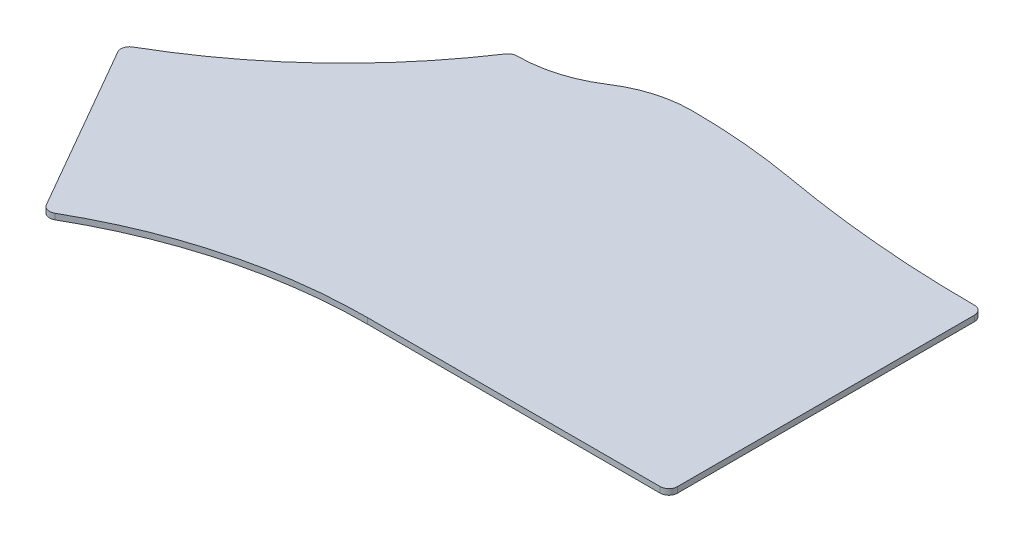
SolidWorks part; units mm, degrees
ref_plane "Front Plane" through (0, 0, 0) normal (0, 0, 1) x (1, 0, 0)
ref_plane "Top Plane" through (0, 0, 0) normal (0, 1, 0) x (1, 0, 0)
ref_plane "Right Plane" through (0, 0, 0) normal (1, 0, 0) x (0, 0, -1)
sketch "Main" plane through (0, 0, 0) normal (0, 1, 0) x (1, 0, 0)
  line L0 (6.4754, 3.5) -> (12.8, 6.5) construction
  line L1 (0, 0) -> (18, 0) construction
  line L2 (0, 0) -> (0, 18) construction
  line L3 (0, 18) -> (18, 18) construction
  line L4 (18, 0) -> (18, 18) construction
  line L5 (2, 16) -> (16, 16)
  line L6 (2, 16) -> (2, 2)
  line L7 (2, 2) -> (16, 2)
  line L8 (16, 16) -> (16, 2)
  line L18 (9, 9) -> (6.4754, 3.5) construction
  line L20 (9, 9) -> (12.8, 6.5) construction
  line L22 (25.4754, 5.5) -> (31.8, 8.5) construction
  line L23 (19, 2) -> (37, 2) construction
  line L24 (19, 2) -> (19, 20) construction
  line L25 (19, 20) -> (37, 20) construction
  line L26 (37, 2) -> (37, 20) construction
  line L27 (21, 18) -> (35, 18)
  line L28 (21, 18) -> (21, 4)
  line L29 (21, 4) -> (35, 4)
  line L30 (35, 18) -> (35, 4)
  line L31 (28, 11) -> (25.4754, 5.5) construction
  line L32 (28, 11) -> (31.8, 8.5) construction
  line L33 (44.4754, 17.5) -> (50.8, 20.5) construction
  line L34 (38, 14) -> (56, 14) construction
  line L35 (38, 14) -> (38, 32) construction
  line L36 (38, 32) -> (56, 32) construction
  line L37 (56, 14) -> (56, 32) construction
  line L38 (40, 30) -> (54, 30)
  line L39 (40, 30) -> (40, 16)
  line L40 (40, 16) -> (54, 16)
  line L41 (54, 30) -> (54, 16)
  line L42 (47, 23) -> (44.4754, 17.5) construction
  line L43 (47, 23) -> (50.8, 20.5) construction
  line L44 (63.4754, 12.5) -> (69.8, 15.5) construction
  line L45 (57, 9) -> (75, 9) construction
  line L46 (57, 9) -> (57, 27) construction
  line L47 (57, 27) -> (75, 27) construction
  line L48 (75, 9) -> (75, 27) construction
  line L49 (59, 25) -> (73, 25)
  line L50 (59, 25) -> (59, 11)
  line L51 (59, 11) -> (73, 11)
  line L52 (73, 25) -> (73, 11)
  line L53 (66, 18) -> (63.4754, 12.5) construction
  line L54 (66, 18) -> (69.8, 15.5) construction
  line L55 (82.4754, 3.5) -> (88.8, 6.5) construction
  line L56 (76, 0) -> (94, 0) construction
  line L57 (76, 0) -> (76, 18) construction
  line L58 (76, 18) -> (94, 18) construction
  line L59 (94, 0) -> (94, 18) construction
  line L60 (78, 16) -> (92, 16)
  line L61 (78, 16) -> (78, 2)
  line L62 (78, 2) -> (92, 2)
  line L63 (92, 16) -> (92, 2)
  line L64 (85, 9) -> (82.4754, 3.5) construction
  line L65 (85, 9) -> (88.8, 6.5) construction
  line L66 (101.4754, -18.5) -> (107.8, -15.5) construction
  line L67 (95, -22) -> (113, -22) construction
  line L68 (95, -22) -> (95, -4) construction
  line L69 (95, -4) -> (113, -4) construction
  line L70 (113, -22) -> (113, -4) construction
  line L71 (97, -6) -> (111, -6)
  line L72 (97, -6) -> (97, -20)
  line L73 (97, -20) -> (111, -20)
  line L74 (111, -6) -> (111, -20)
  line L75 (104, -13) -> (101.4754, -18.5) construction
  line L76 (104, -13) -> (107.8, -15.5) construction
  line L77 (120.4754, -18.5) -> (126.8, -15.5) construction
  line L78 (114, -22) -> (132, -22) construction
  line L79 (114, -22) -> (114, -4) construction
  line L80 (114, -4) -> (132, -4) construction
  line L81 (132, -22) -> (132, -4) construction
  line L82 (116, -6) -> (130, -6)
  line L83 (116, -6) -> (116, -20)
  line L84 (116, -20) -> (130, -20)
  line L85 (130, -6) -> (130, -20)
  line L86 (123, -13) -> (120.4754, -18.5) construction
  line L87 (123, -13) -> (126.8, -15.5) construction
  line L88 (2, -3) -> (16, -3)
  line L89 (2, -3) -> (2, -17)
  line L90 (2, -17) -> (16, -17)
  line L91 (16, -3) -> (16, -17)
  line L92 (21, -1) -> (35, -1)
  line L93 (21, -1) -> (21, -15)
  line L94 (21, -15) -> (35, -15)
  line L95 (35, -1) -> (35, -15)
  line L96 (40, 11) -> (54, 11)
  line L97 (40, 11) -> (40, -3)
  line L98 (40, -3) -> (54, -3)
  line L99 (54, 11) -> (54, -3)
  line L100 (59, 6) -> (73, 6)
  line L101 (59, 6) -> (59, -8)
  line L102 (59, -8) -> (73, -8)
  line L103 (73, 6) -> (73, -8)
  line L104 (78, -3) -> (92, -3)
  line L105 (78, -3) -> (78, -17)
  line L106 (78, -17) -> (92, -17)
  line L107 (92, -3) -> (92, -17)
  line L108 (97, -25) -> (111, -25)
  line L109 (97, -25) -> (97, -39)
  line L110 (97, -39) -> (111, -39)
  line L111 (111, -25) -> (111, -39)
  line L112 (116, -25) -> (130, -25)
  line L113 (116, -25) -> (116, -39)
  line L114 (116, -39) -> (130, -39)
  line L115 (130, -25) -> (130, -39)
  line L116 (6.4754, -15.5) -> (12.8, -12.5) construction
  line L117 (0, -19) -> (18, -19) construction
  line L118 (0, -19) -> (0, -1) construction
  line L119 (0, -1) -> (18, -1) construction
  line L120 (18, -19) -> (18, -1) construction
  line L121 (9, -10) -> (6.4754, -15.5) construction
  line L122 (9, -10) -> (12.8, -12.5) construction
  line L123 (25.4754, -13.5) -> (31.8, -10.5) construction
  line L124 (19, -17) -> (37, -17) construction
  line L125 (19, -17) -> (19, 1) construction
  line L126 (19, 1) -> (37, 1) construction
  line L127 (37, -17) -> (37, 1) construction
  line L128 (28, -8) -> (25.4754, -13.5) construction
  line L129 (28, -8) -> (31.8, -10.5) construction
  line L130 (44.4754, -1.5) -> (50.8, 1.5) construction
  line L131 (38, -5) -> (56, -5) construction
  line L132 (38, -5) -> (38, 13) construction
  line L133 (38, 13) -> (56, 13) construction
  line L134 (56, -5) -> (56, 13) construction
  line L135 (47, 4) -> (44.4754, -1.5) construction
  line L136 (47, 4) -> (50.8, 1.5) construction
  line L137 (63.4754, -6.5) -> (69.8, -3.5) construction
  line L138 (57, -10) -> (75, -10) construction
  line L139 (57, -10) -> (57, 8) construction
  line L140 (57, 8) -> (75, 8) construction
  line L141 (75, -10) -> (75, 8) construction
  line L142 (66, -1) -> (63.4754, -6.5) construction
  line L143 (66, -1) -> (69.8, -3.5) construction
  line L144 (82.4754, -15.5) -> (88.8, -12.5) construction
  line L145 (76, -19) -> (94, -19) construction
  line L146 (76, -19) -> (76, -1) construction
  line L147 (76, -1) -> (94, -1) construction
  line L148 (94, -19) -> (94, -1) construction
  line L149 (85, -10) -> (82.4754, -15.5) construction
  line L150 (85, -10) -> (88.8, -12.5) construction
  line L151 (101.4754, -37.5) -> (107.8, -34.5) construction
  line L152 (95, -41) -> (113, -41) construction
  line L153 (95, -41) -> (95, -23) construction
  line L154 (95, -23) -> (113, -23) construction
  line L155 (113, -41) -> (113, -23) construction
  line L156 (104, -32) -> (101.4754, -37.5) construction
  line L157 (104, -32) -> (107.8, -34.5) construction
  line L158 (120.4754, -37.5) -> (126.8, -34.5) construction
  line L159 (114, -41) -> (132, -41) construction
  line L160 (114, -41) -> (114, -23) construction
  line L161 (114, -23) -> (132, -23) construction
  line L162 (132, -41) -> (132, -23) construction
  line L163 (123, -32) -> (120.4754, -37.5) construction
  line L164 (123, -32) -> (126.8, -34.5) construction
  line L165 (2, -22) -> (16, -22)
  line L166 (2, -22) -> (2, -36)
  line L167 (2, -36) -> (16, -36)
  line L168 (16, -22) -> (16, -36)
  line L169 (21, -20) -> (35, -20)
  line L170 (21, -20) -> (21, -34)
  line L171 (21, -34) -> (35, -34)
  line L172 (35, -20) -> (35, -34)
  line L173 (40, -8) -> (54, -8)
  line L174 (40, -8) -> (40, -22)
  line L175 (40, -22) -> (54, -22)
  line L176 (54, -8) -> (54, -22)
  line L177 (59, -13) -> (73, -13)
  line L178 (59, -13) -> (59, -27)
  line L179 (59, -27) -> (73, -27)
  line L180 (73, -13) -> (73, -27)
  line L181 (78, -22) -> (92, -22)
  line L182 (78, -22) -> (78, -36)
  line L183 (78, -36) -> (92, -36)
  line L184 (92, -22) -> (92, -36)
  line L193 (6.4754, -34.5) -> (12.8, -31.5) construction
  line L194 (0, -38) -> (18, -38) construction
  line L195 (0, -38) -> (0, -20) construction
  line L196 (0, -20) -> (18, -20) construction
  line L197 (18, -38) -> (18, -20) construction
  line L198 (9, -29) -> (6.4754, -34.5) construction
  line L199 (9, -29) -> (12.8, -31.5) construction
  line L200 (25.4754, -32.5) -> (31.8, -29.5) construction
  line L201 (19, -36) -> (37, -36) construction
  line L202 (19, -36) -> (19, -18) construction
  line L203 (19, -18) -> (37, -18) construction
  line L204 (37, -36) -> (37, -18) construction
  line L205 (28, -27) -> (25.4754, -32.5) construction
  line L206 (28, -27) -> (31.8, -29.5) construction
  line L207 (44.4754, -20.5) -> (50.8, -17.5) construction
  line L208 (38, -24) -> (56, -24) construction
  line L209 (38, -24) -> (38, -6) construction
  line L210 (38, -6) -> (56, -6) construction
  line L211 (56, -24) -> (56, -6) construction
  line L212 (47, -15) -> (44.4754, -20.5) construction
  line L213 (47, -15) -> (50.8, -17.5) construction
  line L214 (63.4754, -25.5) -> (69.8, -22.5) construction
  line L215 (57, -29) -> (75, -29) construction
  line L216 (57, -29) -> (57, -11) construction
  line L217 (57, -11) -> (75, -11) construction
  line L218 (75, -29) -> (75, -11) construction
  line L219 (66, -20) -> (63.4754, -25.5) construction
  line L220 (66, -20) -> (69.8, -22.5) construction
  line L221 (82.4754, -34.5) -> (88.8, -31.5) construction
  line L222 (76, -38) -> (94, -38) construction
  line L223 (76, -38) -> (76, -20) construction
  line L224 (76, -20) -> (94, -20) construction
  line L225 (94, -38) -> (94, -20) construction
  line L226 (85, -29) -> (82.4754, -34.5) construction
  line L227 (85, -29) -> (88.8, -31.5) construction
  line L228 (97, 20.5) -> (111, 20.5)
  line L231 (97, 20.5) -> (97, 6.5)
  line L232 (97, 6.5) -> (111, 6.5)
  line L233 (111, 20.5) -> (111, 6.5)
  line L234 (116, 20.5) -> (130, 20.5)
  line L235 (116, 20.5) -> (116, 6.5)
  line L236 (116, 6.5) -> (130, 6.5)
  line L237 (130, 20.5) -> (130, 6.5)
  line L238 (101.4754, 8) -> (107.8, 11) construction
  line L239 (95, 4.5) -> (113, 4.5) construction
  line L240 (95, 4.5) -> (95, 22.5) construction
  line L241 (95, 22.5) -> (113, 22.5) construction
  line L242 (2, -41) -> (16, -41)
  line L243 (2, -41) -> (2, -55)
  line L244 (2, -55) -> (16, -55)
  line L245 (16, -41) -> (16, -55)
  line L246 (21, -39) -> (35, -39)
  line L247 (21, -39) -> (21, -53)
  line L248 (21, -53) -> (35, -53)
  line L249 (35, -39) -> (35, -53)
  line L250 (40, -27) -> (54, -27)
  line L251 (40, -27) -> (40, -41)
  line L252 (40, -41) -> (54, -41)
  line L253 (54, -27) -> (54, -41)
  line L254 (59, -32) -> (73, -32)
  line L255 (59, -32) -> (59, -46)
  line L256 (59, -46) -> (73, -46)
  line L257 (73, -32) -> (73, -46)
  line L258 (78, -41) -> (92, -41)
  line L259 (78, -41) -> (78, -55)
  line L260 (78, -55) -> (92, -55)
  line L261 (92, -41) -> (92, -55)
  line L270 (6.4754, -53.5) -> (12.8, -50.5) construction
  line L271 (0, -57) -> (18, -57) construction
  line L272 (0, -57) -> (0, -39) construction
  line L273 (0, -39) -> (18, -39) construction
  line L274 (18, -57) -> (18, -39) construction
  line L275 (9, -48) -> (6.4754, -53.5) construction
  line L276 (9, -48) -> (12.8, -50.5) construction
  line L277 (25.4754, -51.5) -> (31.8, -48.5) construction
  line L278 (19, -55) -> (37, -55) construction
  line L279 (19, -55) -> (19, -37) construction
  line L280 (19, -37) -> (37, -37) construction
  line L281 (37, -55) -> (37, -37) construction
  line L282 (28, -46) -> (25.4754, -51.5) construction
  line L283 (28, -46) -> (31.8, -48.5) construction
  line L284 (44.4754, -39.5) -> (50.8, -36.5) construction
  line L285 (38, -43) -> (56, -43) construction
  line L286 (38, -43) -> (38, -25) construction
  line L287 (38, -25) -> (56, -25) construction
  line L288 (56, -43) -> (56, -25) construction
  line L289 (47, -34) -> (44.4754, -39.5) construction
  line L290 (47, -34) -> (50.8, -36.5) construction
  line L291 (63.4754, -44.5) -> (69.8, -41.5) construction
  line L292 (57, -48) -> (75, -48) construction
  line L293 (57, -48) -> (57, -30) construction
  line L294 (57, -30) -> (75, -30) construction
  line L295 (75, -48) -> (75, -30) construction
  line L296 (66, -39) -> (63.4754, -44.5) construction
  line L297 (66, -39) -> (69.8, -41.5) construction
  line L298 (82.4754, -53.5) -> (88.8, -50.5) construction
  line L299 (76, -57) -> (94, -57) construction
  line L300 (76, -57) -> (76, -39) construction
  line L301 (76, -39) -> (94, -39) construction
  line L302 (94, -57) -> (94, -39) construction
  line L303 (85, -48) -> (82.4754, -53.5) construction
  line L304 (85, -48) -> (88.8, -50.5) construction
  line L305 (113, 4.5) -> (113, 22.5) construction
  line L306 (104, 13.5) -> (101.4754, 8) construction
  line L307 (104, 13.5) -> (107.8, 11) construction
  line L308 (120.4754, 8) -> (126.8, 11) construction
  line L309 (114, 4.5) -> (132, 4.5) construction
  line L310 (114, 4.5) -> (114, 22.5) construction
  line L311 (114, 22.5) -> (132, 22.5) construction
  line L312 (132, 4.5) -> (132, 22.5) construction
  line L313 (123, 13.5) -> (120.4754, 8) construction
  line L314 (123, 13.5) -> (126.8, 11) construction
  line L319 (97, -63) -> (111, -63)
  line L320 (97, -63) -> (97, -77)
  line L321 (97, -77) -> (111, -77)
  line L322 (111, -63) -> (111, -77)
  line L323 (116, -63) -> (130, -63)
  line L324 (116, -63) -> (116, -77)
  line L325 (116, -77) -> (130, -77)
  line L326 (130, -63) -> (130, -77)
  line L327 (101.4754, -75.5) -> (107.8, -72.5) construction
  line L328 (95, -79) -> (113, -79) construction
  line L329 (95, -79) -> (95, -61) construction
  line L330 (95, -61) -> (113, -61) construction
  line L331 (113, -79) -> (113, -61) construction
  line L332 (104, -70) -> (101.4754, -75.5) construction
  line L333 (104, -70) -> (107.8, -72.5) construction
  line L334 (120.4754, -75.5) -> (126.8, -72.5) construction
  line L335 (114, -79) -> (132, -79) construction
  line L336 (114, -79) -> (114, -61) construction
  line L337 (114, -61) -> (132, -61) construction
  line L338 (132, -79) -> (132, -61) construction
  line L339 (123, -70) -> (120.4754, -75.5) construction
  line L340 (123, -70) -> (126.8, -72.5) construction
  line L341 (97, -44) -> (111, -44)
  line L342 (97, -44) -> (97, -58)
  line L343 (97, -58) -> (111, -58)
  line L344 (111, -44) -> (111, -58)
  line L345 (116, -44) -> (130, -44)
  line L346 (116, -44) -> (116, -58)
  line L347 (116, -58) -> (130, -58)
  line L348 (130, -44) -> (130, -58)
  line L349 (101.4754, -56.5) -> (107.8, -53.5) construction
  line L350 (95, -42) -> (113, -42) construction
  line L351 (113, -60) -> (113, -42) construction
  line L352 (104, -51) -> (101.4754, -56.5) construction
  line L353 (104, -51) -> (107.8, -53.5) construction
  line L354 (120.4754, -56.5) -> (126.8, -53.5) construction
  line L355 (114, -60) -> (132, -60) construction
  line L356 (114, -60) -> (114, -42) construction
  line L357 (114, -42) -> (132, -42) construction
  line L358 (132, -60) -> (132, -42) construction
  line L359 (123, -51) -> (120.4754, -56.5) construction
  line L360 (123, -51) -> (126.8, -53.5) construction
  line L361 (95, -60) -> (113, -60) construction
  line L362 (95, -60) -> (95, -42) construction
  circle A0 centre (9, 9) radius 2 construction
  circle A1 centre (6.4754, 3.5) radius 1.5 construction
  circle A2 centre (12.8, 6.5) radius 1.5 construction
  circle A6 centre (28, 11) radius 2 construction
  circle A7 centre (25.4754, 5.5) radius 1.5 construction
  circle A8 centre (31.8, 8.5) radius 1.5 construction
  circle A9 centre (47, 23) radius 2 construction
  circle A10 centre (44.4754, 17.5) radius 1.5 construction
  circle A11 centre (50.8, 20.5) radius 1.5 construction
  circle A12 centre (66, 18) radius 2 construction
  circle A13 centre (63.4754, 12.5) radius 1.5 construction
  circle A14 centre (69.8, 15.5) radius 1.5 construction
  circle A15 centre (85, 9) radius 2 construction
  circle A16 centre (82.4754, 3.5) radius 1.5 construction
  circle A17 centre (88.8, 6.5) radius 1.5 construction
  circle A18 centre (104, -13) radius 2 construction
  circle A19 centre (101.4754, -18.5) radius 1.5 construction
  circle A20 centre (107.8, -15.5) radius 1.5 construction
  circle A21 centre (123, -13) radius 2 construction
  circle A22 centre (120.4754, -18.5) radius 1.5 construction
  circle A23 centre (126.8, -15.5) radius 1.5 construction
  circle A24 centre (9, -10) radius 2 construction
  circle A25 centre (6.4754, -15.5) radius 1.5 construction
  circle A26 centre (12.8, -12.5) radius 1.5 construction
  circle A27 centre (28, -8) radius 2 construction
  circle A28 centre (25.4754, -13.5) radius 1.5 construction
  circle A29 centre (31.8, -10.5) radius 1.5 construction
  circle A30 centre (47, 4) radius 2 construction
  circle A31 centre (44.4754, -1.5) radius 1.5 construction
  circle A32 centre (50.8, 1.5) radius 1.5 construction
  circle A33 centre (66, -1) radius 2 construction
  circle A34 centre (63.4754, -6.5) radius 1.5 construction
  circle A35 centre (69.8, -3.5) radius 1.5 construction
  circle A36 centre (85, -10) radius 2 construction
  circle A37 centre (82.4754, -15.5) radius 1.5 construction
  circle A38 centre (88.8, -12.5) radius 1.5 construction
  circle A39 centre (104, -32) radius 2 construction
  circle A40 centre (101.4754, -37.5) radius 1.5 construction
  circle A41 centre (107.8, -34.5) radius 1.5 construction
  circle A42 centre (123, -32) radius 2 construction
  circle A43 centre (120.4754, -37.5) radius 1.5 construction
  circle A44 centre (126.8, -34.5) radius 1.5 construction
  circle A45 centre (9, -29) radius 2 construction
  circle A46 centre (6.4754, -34.5) radius 1.5 construction
  circle A47 centre (12.8, -31.5) radius 1.5 construction
  circle A48 centre (28, -27) radius 2 construction
  circle A49 centre (25.4754, -32.5) radius 1.5 construction
  circle A50 centre (31.8, -29.5) radius 1.5 construction
  circle A51 centre (47, -15) radius 2 construction
  circle A52 centre (44.4754, -20.5) radius 1.5 construction
  circle A53 centre (50.8, -17.5) radius 1.5 construction
  circle A54 centre (66, -20) radius 2 construction
  circle A55 centre (63.4754, -25.5) radius 1.5 construction
  circle A56 centre (69.8, -22.5) radius 1.5 construction
  circle A57 centre (85, -29) radius 2 construction
  circle A58 centre (82.4754, -34.5) radius 1.5 construction
  circle A59 centre (88.8, -31.5) radius 1.5 construction
  circle A60 centre (104, 13.5) radius 2 construction
  circle A61 centre (101.4754, 8) radius 1.5 construction
  circle A62 centre (107.8, 11) radius 1.5 construction
  circle A63 centre (123, 13.5) radius 2 construction
  circle A64 centre (120.4754, 8) radius 1.5 construction
  circle A65 centre (126.8, 11) radius 1.5 construction
  circle A66 centre (9, -48) radius 2 construction
  circle A67 centre (6.4754, -53.5) radius 1.5 construction
  circle A68 centre (12.8, -50.5) radius 1.5 construction
  circle A69 centre (28, -46) radius 2 construction
  circle A70 centre (25.4754, -51.5) radius 1.5 construction
  circle A71 centre (31.8, -48.5) radius 1.5 construction
  circle A72 centre (47, -34) radius 2 construction
  circle A73 centre (44.4754, -39.5) radius 1.5 construction
  circle A74 centre (50.8, -36.5) radius 1.5 construction
  circle A75 centre (66, -39) radius 2 construction
  circle A76 centre (63.4754, -44.5) radius 1.5 construction
  circle A77 centre (69.8, -41.5) radius 1.5 construction
  circle A78 centre (85, -48) radius 2 construction
  circle A79 centre (82.4754, -53.5) radius 1.5 construction
  circle A80 centre (88.8, -50.5) radius 1.5 construction
  circle A87 centre (104, -70) radius 2 construction
  circle A88 centre (101.4754, -75.5) radius 1.5 construction
  circle A89 centre (107.8, -72.5) radius 1.5 construction
  circle A90 centre (123, -70) radius 2 construction
  circle A91 centre (120.4754, -75.5) radius 1.5 construction
  circle A92 centre (126.8, -72.5) radius 1.5 construction
  circle A93 centre (104, -51) radius 2 construction
  circle A94 centre (101.4754, -56.5) radius 1.5 construction
  circle A95 centre (107.8, -53.5) radius 1.5 construction
  circle A96 centre (123, -51) radius 2 construction
  circle A97 centre (120.4754, -56.5) radius 1.5 construction
  circle A98 centre (126.8, -53.5) radius 1.5 construction
  point P9 (9, 16)
  point P10 (9, 18)
  point P11 (2, 9)
  point P12 (0, 9)
  point P30 (28, 18)
  point P31 (28, 20)
  point P32 (21, 11)
  point P33 (19, 11)
  point P46 (47, 30)
  point P47 (47, 32)
  point P48 (40, 23)
  point P49 (38, 23)
  point P64 (66, 25)
  point P65 (66, 27)
  point P66 (59, 18)
  point P67 (57, 18)
  point P82 (85, 16)
  point P83 (85, 18)
  point P84 (78, 9)
  point P85 (76, 9)
  point P100 (104, -6)
  point P101 (104, -4)
  point P102 (97, -13)
  point P103 (95, -13)
  point P118 (123, -6)
  point P119 (123, -4)
  point P120 (116, -13)
  point P121 (114, -13)
  dimension "D6" = 4
  dimension "D7" = 3
  dimension "D10" = 1
  dimension "D11" = 5
  dimension "D1" = 18
  dimension "D2" = 14
  dimension "D3" = 3.2
  dimension "D4" = 4.5
  dimension "D5" = 7
  dimension "D8" = 1
  dimension "D9" = 12
  dimension "D12" = 1
  dimension "D13" = 2
  dimension "D14" = 1
  dimension "D15" = 9
  dimension "D16" = 1
  dimension "D17" = 3
  dimension "D18" = 1
  dimension "D20" = 1
  dimension "D22" = 4.5
  dimension "D19" = 4
  dimension "D21" = 2
sketch "EntBckSp" plane through (0, 0, 0) normal (0, 1, 0) x (1, 0, 0)
  line L0 (0, 0) -> (18, 0) construction
  line L1 (139, 11.25) -> (153, 11.25)
  line L2 (139, 11.25) -> (139, -2.75)
  line L3 (139, -2.75) -> (153, -2.75)
  line L4 (153, 11.25) -> (153, -2.75)
  line L5 (137, 18) -> (155, 18) construction
  line L6 (137, 18) -> (137, -9.5) construction
  line L7 (137, -9.5) -> (155, -9.5) construction
  line L8 (155, 18) -> (155, -9.5) construction
  line L9 (2, 2) -> (16, 2) construction
  line L10 (143.4754, -1.25) -> (146, 4.25) construction
  line L11 (146, 4.25) -> (149.8, 1.75) construction
  line L12 (149.8, 1.75) -> (143.4754, -1.25) construction
  line L13 (6.4754, 3.5) -> (12.8, 6.5) construction
  line L14 (9, 9) -> (6.4754, 3.5) construction
  line L15 (9, 9) -> (12.8, 6.5) construction
  line L17 (132, -22) -> (132, -4) construction
  line L18 (101.75, -44) -> (115.75, -44)
  line L19 (101.75, -44) -> (101.75, -58)
  line L20 (101.75, -58) -> (115.75, -58)
  line L21 (115.75, -44) -> (115.75, -58)
  line L22 (95, -42) -> (122.5, -42) construction
  line L23 (95, -42) -> (95, -60) construction
  line L24 (95, -60) -> (122.5, -60) construction
  line L25 (122.5, -42) -> (122.5, -60) construction
  line L26 (106.2254, -56.5) -> (108.75, -51) construction
  line L27 (108.75, -51) -> (112.55, -53.5) construction
  line L28 (112.55, -53.5) -> (106.2254, -56.5) construction
  line L29 (0, 18) -> (18, 18) construction
  line L30 (46.5, -79) -> (28.5, -79) construction
  line L31 (101.75, -63) -> (115.75, -63)
  line L32 (101.75, -63) -> (101.75, -77)
  line L33 (101.75, -77) -> (115.75, -77)
  line L34 (115.75, -63) -> (115.75, -77)
  line L35 (95, -61) -> (122.5, -61) construction
  line L36 (95, -61) -> (95, -79) construction
  line L37 (95, -79) -> (122.5, -79) construction
  line L38 (122.5, -61) -> (122.5, -79) construction
  line L39 (106.2254, -75.5) -> (108.75, -70) construction
  line L40 (108.75, -70) -> (112.55, -72.5) construction
  line L41 (112.55, -72.5) -> (106.2254, -75.5) construction
  line L42 (139, -58.25) -> (153, -58.25)
  line L43 (139, -58.25) -> (139, -72.25)
  line L44 (139, -72.25) -> (153, -72.25)
  line L45 (153, -58.25) -> (153, -72.25)
  line L46 (137, -51.5) -> (155, -51.5) construction
  line L47 (137, -51.5) -> (137, -79) construction
  line L48 (137, -79) -> (155, -79) construction
  line L49 (155, -51.5) -> (155, -79) construction
  line L50 (143.4754, -70.75) -> (146, -65.25) construction
  line L51 (146, -65.25) -> (149.8, -67.75) construction
  line L52 (149.8, -67.75) -> (143.4754, -70.75) construction
  line L64 (95, -41) -> (95, -23) construction
  line L65 (114, -41) -> (132, -41) construction
  line L66 (6.75, -63) -> (20.75, -63)
  line L67 (6.75, -63) -> (6.75, -77)
  line L68 (6.75, -77) -> (20.75, -77)
  line L69 (20.75, -63) -> (20.75, -77)
  line L70 (0, -61) -> (27.5, -61) construction
  line L71 (0, -61) -> (0, -79) construction
  line L72 (0, -79) -> (27.5, -79) construction
  line L73 (27.5, -61) -> (27.5, -79) construction
  line L74 (11.2254, -75.5) -> (13.75, -70) construction
  line L75 (13.75, -70) -> (17.55, -72.5) construction
  line L76 (17.55, -72.5) -> (11.2254, -75.5) construction
  line L78 (0, -57) -> (0, -39) construction
  line L80 (30.5, -63) -> (44.5, -63)
  line L81 (30.5, -63) -> (30.5, -77)
  line L82 (30.5, -77) -> (44.5, -77)
  line L83 (44.5, -63) -> (44.5, -77)
  line L86 (34.9754, -75.5) -> (37.5, -70) construction
  line L87 (37.5, -70) -> (41.3, -72.5) construction
  line L88 (41.3, -72.5) -> (34.9754, -75.5) construction
  line L91 (51.25, -61) -> (51.25, -79) construction
  line L92 (23.75, -61) -> (23.75, -79) construction
  line L93 (46.5, -79) -> (46.5, -61) construction
  line L94 (46.5, -61) -> (28.5, -61) construction
  line L95 (28.5, -79) -> (28.5, -61) construction
  circle A0 centre (146, 4.25) radius 2 construction
  circle A1 centre (143.4754, -1.25) radius 1.5 construction
  circle A2 centre (149.8, 1.75) radius 1.5 construction
  circle A3 centre (9, 9) radius 2 construction
  circle A4 centre (6.4754, 3.5) radius 1.5 construction
  circle A5 centre (108.75, -51) radius 2 construction
  circle A6 centre (106.2254, -56.5) radius 1.5 construction
  circle A7 centre (112.55, -53.5) radius 1.5 construction
  circle A8 centre (108.75, -70) radius 2 construction
  circle A9 centre (106.2254, -75.5) radius 1.5 construction
  circle A10 centre (112.55, -72.5) radius 1.5 construction
  circle A11 centre (146, -65.25) radius 2 construction
  circle A12 centre (143.4754, -70.75) radius 1.5 construction
  circle A13 centre (149.8, -67.75) radius 1.5 construction
  circle A17 centre (13.75, -70) radius 2 construction
  circle A18 centre (11.2254, -75.5) radius 1.5 construction
  circle A19 centre (17.55, -72.5) radius 1.5 construction
  circle A20 centre (37.5, -70) radius 2 construction
  circle A21 centre (34.9754, -75.5) radius 1.5 construction
  circle A22 centre (41.3, -72.5) radius 1.5 construction
  point P14 (146, 11.25)
  point P15 (146, 18)
  point P16 (139, 4.25)
  point P17 (137, 4.25)
  point P51 (108.75, -44)
  point P52 (108.75, -42)
  point P53 (101.75, -51)
  point P54 (95, -51)
  point P87 (146, -58.25)
  point P88 (146, -51.5)
  point P89 (139, -65.25)
  point P90 (137, -65.25)
  point P105 (13.75, -63)
  point P106 (13.75, -61)
  point P107 (6.75, -70)
  point P108 (0, -70)
  point P109 (37.5, -63)
  point P132 (37.5, -61)
  dimension "D1" = 27.5
  dimension "D2" = 5
  dimension "D3" = 1
  dimension "D5" = 1
  dimension "D6" = 2
  dimension "D7" = 1
  dimension "D4" = 2
sketch "MoLng" plane through (0, 0, 0) normal (0, 1, 0) x (1, 0, 0)
  line L0 (-25.7133, -75.4047) -> (-13.5763, -68.4267)
  line L1 (-25.7133, -75.4047) -> (-18.7353, -87.5417)
  line L2 (-13.5763, -68.4267) -> (-6.5983, -80.5637)
  line L3 (-18.7353, -87.5417) -> (-6.5983, -80.5637)
  line L4 (-30.8116, -70.5498) -> (-15.2068, -61.578) construction
  line L5 (-30.8116, -70.5498) -> (-17.1047, -94.3903) construction
  line L6 (-15.2068, -61.578) -> (-1.5, -85.4186) construction
  line L7 (-17.1047, -94.3903) -> (-1.5, -85.4186) construction
  line L8 (-15.2068, -61.578) -> (-17.1047, -94.3903) construction
  line L9 (-25.7133, -75.4047) -> (-6.5983, -80.5637) construction
  line L10 (0, -61) -> (0, -79) construction
  line L11 (0, -79) -> (27.5, -79) construction
  line L12 (6.75, -77) -> (20.75, -77) construction
  line L13 (-16.1558, -77.9842) -> (13.75, -130) construction
  line L14 (-15.603, -84.0106) -> (-11.6154, -78.2575) construction
  line L15 (-11.6154, -78.2575) -> (-16.1558, -77.9842) construction
  line L16 (-16.1558, -77.9842) -> (-15.603, -84.0106) construction
  line L17 (17.55, -72.5) -> (11.2254, -75.5) construction
  line L18 (11.2254, -75.5) -> (13.75, -70) construction
  line L19 (13.75, -70) -> (17.55, -72.5) construction
  line L20 (-43.0519, -85.3733) -> (-30.9149, -78.3953)
  line L21 (-43.0519, -85.3733) -> (-36.0739, -97.5103)
  line L22 (-30.9149, -78.3953) -> (-23.9369, -90.5323)
  line L23 (-36.0739, -97.5103) -> (-23.9369, -90.5323)
  line L24 (-48.1502, -80.5184) -> (-32.5454, -71.5466) construction
  line L25 (-48.1502, -80.5184) -> (-34.4433, -104.3589) construction
  line L26 (-32.5454, -71.5466) -> (-18.8386, -95.3872) construction
  line L27 (-34.4433, -104.3589) -> (-18.8386, -95.3872) construction
  line L28 (-32.5454, -71.5466) -> (-34.4433, -104.3589) construction
  line L29 (-43.0519, -85.3733) -> (-23.9369, -90.5323) construction
  line L31 (-32.9416, -93.9792) -> (-28.954, -88.2261) construction
  line L32 (-28.954, -88.2261) -> (-33.4944, -87.9528) construction
  line L33 (-33.4944, -87.9528) -> (-32.9416, -93.9792) construction
  line L38 (-48.9084, -75.1869) -> (-55.8865, -63.0498)
  line L39 (-48.9084, -75.1869) -> (-36.7714, -68.2088)
  line L43 (-55.8865, -63.0498) -> (-43.7494, -56.0718)
  line L51 (-36.7714, -68.2088) -> (-43.7494, -56.0718)
  line L52 (-48.9084, -75.1869) -> (-43.7494, -56.0718) construction
  line L56 (-55.8865, -63.0498) -> (-36.7714, -68.2088) construction
  line L57 (2, -55) -> (16, -55) construction
  line L58 (-45.7762, -71.6558) -> (-41.7885, -65.9026) construction
  line L59 (-41.7885, -65.9026) -> (-46.3289, -65.6293) construction
  line L66 (-46.3289, -65.6293) -> (-45.7762, -71.6558) construction
  line L69 (9, -48) -> (12.8, -50.5) construction
  line L70 (6.4754, -53.5) -> (12.8, -50.5) construction
  line L71 (9, -48) -> (6.4754, -53.5) construction
  line L73 (-49.6455, -77.9176) -> (-58.6172, -62.3128) construction
  line L104 (-49.6455, -77.9176) -> (-34.0407, -68.9458) construction
  line L134 (-58.6172, -62.3128) -> (-43.0124, -53.3411) construction
  line L135 (-34.0407, -68.9458) -> (-43.0124, -53.3411) construction
  line L136 (-49.6455, -77.9176) -> (-43.0124, -53.3411) construction
  line L137 (-58.6172, -62.3128) -> (-34.0407, -68.9458) construction
  line L158 (0, -57) -> (18, -57) construction
  line L162 (-32.4368, -65.7167) -> (-39.4148, -53.5797)
  line L163 (-32.4368, -65.7167) -> (-20.2998, -58.7387)
  line L170 (-39.4148, -53.5797) -> (-27.2778, -46.6017)
  line L171 (-20.2998, -58.7387) -> (-27.2778, -46.6017)
  line L174 (-32.4368, -65.7167) -> (-27.2778, -46.6017) construction
  line L175 (-39.4148, -53.5797) -> (-20.2998, -58.7387) construction
  line L176 (-29.3045, -62.1856) -> (-25.3169, -56.4325) construction
  line L177 (-25.3169, -56.4325) -> (-29.8573, -56.1592) construction
  line L180 (-29.8573, -56.1592) -> (-29.3045, -62.1856) construction
  line L181 (-33.1738, -68.4474) -> (-42.1455, -52.8427) construction
  line L182 (-33.1738, -68.4474) -> (-17.569, -59.4757) construction
  line L183 (-42.1455, -52.8427) -> (-26.5408, -43.8709) construction
  line L184 (-17.569, -59.4757) -> (-26.5408, -43.8709) construction
  line L185 (-33.1738, -68.4474) -> (-26.5408, -43.8709) construction
  line L190 (-42.1455, -52.8427) -> (-17.569, -59.4757) construction
  line L191 (-15.9651, -56.2465) -> (-22.9431, -44.1095)
  line L192 (-15.9651, -56.2465) -> (-3.8281, -49.2685)
  line L193 (-22.9431, -44.1095) -> (-10.8061, -37.1315)
  line L194 (-3.8281, -49.2685) -> (-10.8061, -37.1315)
  line L195 (-15.9651, -56.2465) -> (-10.8061, -37.1315) construction
  line L196 (-22.9431, -44.1095) -> (-3.8281, -49.2685) construction
  line L197 (-12.8328, -52.7154) -> (-8.8452, -46.9623) construction
  line L198 (-8.8452, -46.9623) -> (-13.3856, -46.689) construction
  line L199 (-13.3856, -46.689) -> (-12.8328, -52.7154) construction
  line L200 (-16.7021, -58.9772) -> (-25.6738, -43.3725) construction
  line L201 (-16.7021, -58.9772) -> (-1.0974, -50.0055) construction
  line L202 (-25.6738, -43.3725) -> (-10.0691, -34.4008) construction
  line L203 (-1.0974, -50.0055) -> (-10.0691, -34.4008) construction
  line L204 (-16.7021, -58.9772) -> (-10.0691, -34.4008) construction
  line L205 (-25.6738, -43.3725) -> (-1.0974, -50.0055) construction
  line L206 (-41.9069, -49.245) -> (-48.885, -37.108)
  line L207 (-41.9069, -49.245) -> (-29.7699, -42.267)
  line L208 (-48.885, -37.108) -> (-36.7479, -30.13)
  line L209 (-29.7699, -42.267) -> (-36.7479, -30.13)
  line L210 (-41.9069, -49.245) -> (-36.7479, -30.13) construction
  line L211 (-48.885, -37.108) -> (-29.7699, -42.267) construction
  line L212 (-38.7747, -45.7139) -> (-34.787, -39.9608) construction
  line L213 (-34.787, -39.9608) -> (-39.3274, -39.6875) construction
  line L214 (-39.3274, -39.6875) -> (-38.7747, -45.7139) construction
  line L215 (-42.6439, -51.9757) -> (-51.6157, -36.371) construction
  line L216 (-42.6439, -51.9757) -> (-27.0392, -43.004) construction
  line L217 (-51.6157, -36.371) -> (-36.0109, -27.3993) construction
  line L218 (-27.0392, -43.004) -> (-36.0109, -27.3993) construction
  line L219 (-42.6439, -51.9757) -> (-36.0109, -27.3993) construction
  line L220 (-51.6157, -36.371) -> (-27.0392, -43.004) construction
  line L221 (-25.4353, -39.7749) -> (-32.4133, -27.6378)
  line L222 (-25.4353, -39.7749) -> (-13.2982, -32.7968)
  line L223 (-32.4133, -27.6378) -> (-20.2763, -20.6598)
  line L224 (-13.2982, -32.7968) -> (-20.2763, -20.6598)
  line L225 (-25.4353, -39.7749) -> (-20.2763, -20.6598) construction
  line L226 (-32.4133, -27.6378) -> (-13.2982, -32.7968) construction
  line L227 (-22.303, -36.2438) -> (-18.3154, -30.4906) construction
  line L228 (-18.3154, -30.4906) -> (-22.8558, -30.2173) construction
  line L229 (-22.8558, -30.2173) -> (-22.303, -36.2438) construction
  line L230 (-26.1723, -42.5056) -> (-35.144, -26.9008) construction
  line L231 (-26.1723, -42.5056) -> (-10.5675, -33.5338) construction
  line L232 (-35.144, -26.9008) -> (-19.5393, -17.9291) construction
  line L233 (-10.5675, -33.5338) -> (-19.5393, -17.9291) construction
  line L234 (-26.1723, -42.5056) -> (-19.5393, -17.9291) construction
  line L235 (-35.144, -26.9008) -> (-10.5675, -33.5338) construction
  line L236 (-58.3786, -58.7152) -> (-65.3566, -46.5782)
  line L237 (-58.3786, -58.7152) -> (-46.2416, -51.7372)
  line L238 (-65.3566, -46.5782) -> (-53.2196, -39.6001)
  line L239 (-46.2416, -51.7372) -> (-53.2196, -39.6001)
  line L240 (-58.3786, -58.7152) -> (-53.2196, -39.6001) construction
  line L241 (-65.3566, -46.5782) -> (-46.2416, -51.7372) construction
  line L242 (-55.2464, -55.1841) -> (-51.2587, -49.431) construction
  line L243 (-51.2587, -49.431) -> (-55.7991, -49.1577) construction
  line L244 (-55.7991, -49.1577) -> (-55.2464, -55.1841) construction
  line L245 (-59.1156, -61.4459) -> (-68.0873, -45.8412) construction
  line L246 (-59.1156, -61.4459) -> (-43.5109, -52.4742) construction
  line L247 (-68.0873, -45.8412) -> (-52.4826, -36.8694) construction
  line L248 (-43.5109, -52.4742) -> (-52.4826, -36.8694) construction
  line L249 (-59.1156, -61.4459) -> (-52.4826, -36.8694) construction
  line L250 (-68.0873, -45.8412) -> (-43.5109, -52.4742) construction
  circle A0 centre (13.75, -130) radius 60 construction
  circle A1 centre (-16.1558, -77.9842) radius 2 construction
  circle A2 centre (13.75, -70) radius 2 construction
  circle A3 centre (-15.603, -84.0106) radius 1.5 construction
  circle A4 centre (-11.6154, -78.2575) radius 1.5 construction
  circle A5 centre (11.2254, -75.5) radius 1.5 construction
  circle A6 centre (-33.4944, -87.9528) radius 2 construction
  circle A7 centre (-32.9416, -93.9792) radius 1.5 construction
  circle A8 centre (-28.954, -88.2261) radius 1.5 construction
  circle A12 centre (-46.3289, -65.6293) radius 2 construction
  circle A13 centre (-45.7762, -71.6558) radius 1.5 construction
  circle A14 centre (-41.7885, -65.9026) radius 1.5 construction
  circle A15 centre (6.4754, -53.5) radius 1.5 construction
  circle A16 centre (9, -48) radius 2 construction
  circle A17 centre (-29.8573, -56.1592) radius 2 construction
  circle A18 centre (-25.3169, -56.4325) radius 1.5 construction
  circle A19 centre (-29.3045, -62.1856) radius 1.5 construction
  circle A20 centre (-13.3856, -46.689) radius 2 construction
  circle A24 centre (-8.8452, -46.9623) radius 1.5 construction
  circle A25 centre (-12.8328, -52.7154) radius 1.5 construction
  circle A26 centre (-39.3274, -39.6875) radius 2 construction
  circle A27 centre (-34.787, -39.9608) radius 1.5 construction
  circle A28 centre (-38.7747, -45.7139) radius 1.5 construction
  circle A29 centre (-22.8558, -30.2173) radius 2 construction
  circle A30 centre (-18.3154, -30.4906) radius 1.5 construction
  circle A31 centre (-22.303, -36.2438) radius 1.5 construction
  circle A32 centre (-55.7991, -49.1577) radius 2 construction
  circle A35 centre (-51.2587, -49.431) radius 1.5 construction
  circle A36 centre (-55.2464, -55.1841) radius 1.5 construction
  point P2 (-16.1558, -77.9842)
  point P11 (-16.1558, -77.9842)
  point P28 (-46.3289, -65.6293)
  point P39 (-33.4944, -87.9528)
  point P46 (-33.4944, -87.9528)
  point P89 (-29.8573, -56.1592)
  point P112 (-13.3856, -46.689)
  point P134 (-39.3274, -39.6875)
  point P155 (-22.8558, -30.2173)
  point P170 (-55.7991, -49.1577)
  dimension "D1" = 120
  dimension "D2" = 2
  dimension "D4" = 2
  dimension "D5" = 3
  dimension "D6" = 1.5
  dimension "D8" = 1
  dimension "D3" = 3
  dimension "D7" = 1
sketch "Sketch3" plane through (0, 0, 0) normal (0, 1, 0) x (1, 0, 0)
  line L1 (160, 22.5) -> (160, -81) construction
  line L2 (155, -86) -> (53.0505, -86) construction
  line L6 (158, 22.5) -> (158, -81)
  line L8 (-34.4433, -104.3589) -> (-31.9512, -108.6936) construction
  line L9 (155, -51.5) -> (155, -79) construction
  line L10 (-48.1502, -80.5184) -> (-34.4433, -104.3589) construction
  line L11 (-34.4433, -104.3589) -> (-18.8386, -95.3872) construction
  line L12 (-38.778, -106.8511) -> (-72.422, -48.3333) construction
  line L13 (137, -79) -> (155, -79) construction
  line L15 (38, 32) -> (56, 32) construction
  line L16 (47, 37) -> (160, 37) construction
  line L18 (97, 20.5) -> (111, 20.5) construction
  line L19 (-65.3566, -46.5782) -> (-53.2196, -39.6001) construction
  line L21 (155, -84) -> (53.0505, -84)
  line L22 (2, -3) -> (16, -3) construction
  line L23 (2, 16) -> (16, 16) construction
  line L24 (2, 16) -> (2, 2) construction
  line L25 (2, 2) -> (16, 2) construction
  line L26 (16, 16) -> (16, 2) construction
  line L27 (21, 18) -> (35, 18) construction
  line L28 (21, 18) -> (21, 4) construction
  line L29 (21, 4) -> (35, 4) construction
  line L30 (35, 18) -> (35, 4) construction
  line L31 (40, 30) -> (54, 30) construction
  line L32 (40, 30) -> (40, 16) construction
  line L33 (40, 16) -> (54, 16) construction
  line L34 (54, 30) -> (54, 16) construction
  line L35 (59, 25) -> (73, 25) construction
  line L36 (59, 25) -> (59, 11) construction
  line L37 (59, 11) -> (73, 11) construction
  line L38 (73, 25) -> (73, 11) construction
  line L39 (78, 16) -> (92, 16) construction
  line L40 (78, 16) -> (78, 2) construction
  line L41 (78, 2) -> (92, 2) construction
  line L42 (92, 16) -> (92, 2) construction
  line L43 (97, -6) -> (111, -6) construction
  line L44 (97, -6) -> (97, -20) construction
  line L45 (97, -20) -> (111, -20) construction
  line L46 (111, -6) -> (111, -20) construction
  line L47 (116, -6) -> (130, -6) construction
  line L48 (116, -6) -> (116, -20) construction
  line L49 (116, -20) -> (130, -20) construction
  line L50 (130, -6) -> (130, -20) construction
  line L51 (139, 11.25) -> (153, 11.25) construction
  line L52 (139, 11.25) -> (139, -2.75) construction
  line L53 (139, -2.75) -> (153, -2.75) construction
  line L54 (153, 11.25) -> (153, -2.75) construction
  line L55 (139, -58.25) -> (153, -58.25) construction
  line L56 (139, -58.25) -> (139, -72.25) construction
  line L57 (139, -72.25) -> (153, -72.25) construction
  line L58 (153, -58.25) -> (153, -72.25) construction
  line L59 (2, -3) -> (2, -17) construction
  line L60 (2, -17) -> (16, -17) construction
  line L61 (16, -3) -> (16, -17) construction
  line L62 (21, -1) -> (35, -1) construction
  line L63 (21, -1) -> (21, -15) construction
  line L64 (21, -15) -> (35, -15) construction
  line L65 (35, -1) -> (35, -15) construction
  line L66 (40, 11) -> (54, 11) construction
  line L67 (40, 11) -> (40, -3) construction
  line L68 (40, -3) -> (54, -3) construction
  line L69 (54, 11) -> (54, -3) construction
  line L70 (59, 6) -> (73, 6) construction
  line L71 (59, 6) -> (59, -8) construction
  line L72 (59, -8) -> (73, -8) construction
  line L73 (73, 6) -> (73, -8) construction
  line L74 (78, -3) -> (92, -3) construction
  line L75 (78, -3) -> (78, -17) construction
  line L76 (78, -17) -> (92, -17) construction
  line L77 (92, -3) -> (92, -17) construction
  line L78 (97, -25) -> (111, -25) construction
  line L79 (97, -25) -> (97, -39) construction
  line L80 (97, -39) -> (111, -39) construction
  line L81 (111, -25) -> (111, -39) construction
  line L82 (116, -25) -> (130, -25) construction
  line L83 (116, -25) -> (116, -39) construction
  line L84 (116, -39) -> (130, -39) construction
  line L85 (130, -25) -> (130, -39) construction
  line L86 (2, -22) -> (16, -22) construction
  line L87 (2, -22) -> (2, -36) construction
  line L88 (2, -36) -> (16, -36) construction
  line L89 (16, -22) -> (16, -36) construction
  line L90 (21, -20) -> (35, -20) construction
  line L91 (21, -20) -> (21, -34) construction
  line L92 (21, -34) -> (35, -34) construction
  line L93 (35, -20) -> (35, -34) construction
  line L94 (40, -8) -> (54, -8) construction
  line L95 (40, -8) -> (40, -22) construction
  line L96 (40, -22) -> (54, -22) construction
  line L97 (54, -8) -> (54, -22) construction
  line L98 (59, -13) -> (73, -13) construction
  line L99 (59, -13) -> (59, -27) construction
  line L100 (59, -27) -> (73, -27) construction
  line L101 (73, -13) -> (73, -27) construction
  line L102 (78, -22) -> (92, -22) construction
  line L103 (78, -22) -> (78, -36) construction
  line L104 (78, -36) -> (92, -36) construction
  line L105 (92, -22) -> (92, -36) construction
  line L114 (2, -41) -> (16, -41) construction
  line L115 (2, -41) -> (2, -55) construction
  line L116 (2, -55) -> (16, -55) construction
  line L117 (16, -41) -> (16, -55) construction
  line L118 (21, -39) -> (35, -39) construction
  line L119 (21, -39) -> (21, -53) construction
  line L120 (21, -53) -> (35, -53) construction
  line L121 (35, -39) -> (35, -53) construction
  line L122 (40, -27) -> (54, -27) construction
  line L123 (40, -27) -> (40, -41) construction
  line L124 (40, -41) -> (54, -41) construction
  line L125 (54, -27) -> (54, -41) construction
  line L126 (59, -32) -> (73, -32) construction
  line L127 (59, -32) -> (59, -46) construction
  line L128 (59, -46) -> (73, -46) construction
  line L129 (73, -32) -> (73, -46) construction
  line L130 (78, -41) -> (92, -41) construction
  line L131 (78, -41) -> (78, -55) construction
  line L132 (78, -55) -> (92, -55) construction
  line L133 (92, -41) -> (92, -55) construction
  line L142 (97, -63) -> (111, -63) [skipped]
  line L143 (97, -63) -> (97, -77) [skipped]
  line L144 (97, -77) -> (111, -77) [skipped]
  line L145 (111, -63) -> (111, -77) [skipped]
  line L146 (116, -63) -> (130, -63) [skipped]
  line L147 (116, -63) -> (116, -77) [skipped]
  line L148 (116, -77) -> (130, -77) [skipped]
  line L149 (130, -63) -> (130, -77) [skipped]
  line L151 (6.75, -63) -> (20.75, -63) construction
  line L152 (6.75, -63) -> (6.75, -77) construction
  line L153 (6.75, -77) -> (20.75, -77) construction
  line L154 (20.75, -63) -> (20.75, -77) construction
  line L159 (101.75, -63) -> (115.75, -63) construction
  line L160 (101.75, -63) -> (101.75, -77) construction
  line L161 (101.75, -77) -> (115.75, -77) construction
  line L162 (115.75, -63) -> (115.75, -77) construction
  line L186 (-70.5795, -41.5065) -> (0, -0.9278) construction
  line L187 (-30.9149, -78.3953) -> (-43.0519, -85.3733) construction
  line L188 (-30.9149, -78.3953) -> (-23.9369, -90.5323) construction
  line L189 (-43.0519, -85.3733) -> (-36.0739, -97.5103) construction
  line L190 (-23.9369, -90.5323) -> (-36.0739, -97.5103) construction
  line L191 (-25.7133, -75.4047) -> (-13.5763, -68.4267) construction
  line L192 (-25.7133, -75.4047) -> (-18.7353, -87.5417) construction
  line L193 (-13.5763, -68.4267) -> (-6.5983, -80.5637) construction
  line L194 (-18.7353, -87.5417) -> (-6.5983, -80.5637) construction
  line L196 (97, 20.5) -> (97, 6.5) construction
  line L201 (97, 6.5) -> (111, 6.5) construction
  line L207 (97, -44) -> (111, -44) [skipped]
  line L208 (97, -44) -> (97, -58) [skipped]
  line L209 (97, -58) -> (111, -58) [skipped]
  line L210 (111, -44) -> (111, -58) [skipped]
  line L211 (116, -44) -> (130, -44) [skipped]
  line L212 (116, -44) -> (116, -58) [skipped]
  line L213 (116, -58) -> (130, -58) [skipped]
  line L214 (130, -44) -> (130, -58) [skipped]
  line L215 (111, 20.5) -> (111, 6.5) construction
  line L216 (116, 20.5) -> (130, 20.5) construction
  line L217 (116, 20.5) -> (116, 6.5) construction
  line L218 (116, 6.5) -> (130, 6.5) construction
  line L219 (130, 20.5) -> (130, 6.5) construction
  line L220 (30.5, -63) -> (44.5, -63) construction
  line L221 (30.5, -63) -> (30.5, -77) construction
  line L222 (30.5, -77) -> (44.5, -77) construction
  line L223 (44.5, -63) -> (44.5, -77) construction
  line L224 (101.75, -44) -> (115.75, -44) construction
  line L225 (101.75, -44) -> (101.75, -58) construction
  line L226 (101.75, -58) -> (115.75, -58) construction
  line L227 (115.75, -44) -> (115.75, -58) construction
  line L241 (155, 27.5) -> (56, 27.5) construction
  line L246 (56, 14) -> (56, 32) construction
  line L247 (47, 37) -> (47, 32) construction
  line L248 (-35.144, -26.9008) -> (-19.5393, -17.9291) construction
  line L249 (-65.3566, -46.5782) -> (-58.3786, -58.7152) construction
  line L251 (-53.2196, -39.6001) -> (-46.2416, -51.7372) construction
  line L252 (0, -19) -> (0, -1) construction
  line L253 (-58.3786, -58.7152) -> (-46.2416, -51.7372) construction
  line L254 (-55.8865, -63.0498) -> (-43.7494, -56.0718) construction
  line L255 (-55.8865, -63.0498) -> (-48.9084, -75.1869) construction
  line L256 (-43.7494, -56.0718) -> (-36.7714, -68.2088) construction
  line L257 (-48.9084, -75.1869) -> (-36.7714, -68.2088) construction
  line L258 (-48.885, -37.108) -> (-36.7479, -30.13) construction
  line L260 (-48.885, -37.108) -> (-41.9069, -49.245) construction
  line L261 (-36.7479, -30.13) -> (-29.7699, -42.267) construction
  line L262 (85, 33.6574) -> (85, 16) construction
  line L263 (-41.9069, -49.245) -> (-29.7699, -42.267) construction
  line L264 (-32.4133, -27.6378) -> (-20.2763, -20.6598) construction
  line L265 (-32.4133, -27.6378) -> (-25.4353, -39.7749) construction
  line L266 (-20.2763, -20.6598) -> (-13.2982, -32.7968) construction
  line L267 (-25.4353, -39.7749) -> (-13.2982, -32.7968) construction
  line L268 (-22.9431, -44.1095) -> (-10.8061, -37.1315) construction
  line L269 (-22.9431, -44.1095) -> (-15.9651, -56.2465) construction
  line L270 (-10.8061, -37.1315) -> (-3.8281, -49.2685) construction
  line L271 (-15.9651, -56.2465) -> (-3.8281, -49.2685) construction
  line L272 (-39.4148, -53.5797) -> (-27.2778, -46.6017) construction
  line L273 (-39.4148, -53.5797) -> (-32.4368, -65.7167) construction
  line L274 (-27.2778, -46.6017) -> (-20.2998, -58.7387) construction
  line L275 (-32.4368, -65.7167) -> (-20.2998, -58.7387) construction
  line L276 (-37.0441, -105.8542) -> (-70.6881, -47.3364)
  line L277 (114, 22.5) -> (132, 22.5) construction
  arc A3 (23.5, 30) -> (47, 37) centre (47, -5.9464) cw construction
  arc A21 (-72.422, -48.3333) -> (-70.5795, -41.5065) centre (-68.0873, -45.8412) cw construction
  arc A24 (-70.5795, -41.5065) -> (-4.1654, 20.7657) centre (-169.4955, 130.5404) ccw construction
  arc A25 (0, 23) -> (23.5, 30) centre (0, 65.9464) ccw construction
  arc A26 (47, 37) -> (85, 33.6574) centre (47, -180.6713) cw construction
  arc A27 (85, 33.6574) -> (155, 27.5) centre (155, 428.4734) ccw construction
  arc A28 (-31.9512, -108.6936) -> (53.0505, -86) centre (53.0505, -256.5389) cw construction
  arc A29 (-38.778, -106.8511) -> (-31.9512, -108.6936) centre (-34.4433, -104.3589) ccw construction
  arc A30 (155, -86) -> (160, -81) centre (155, -81) ccw construction
  arc A31 (160, 22.5) -> (155, 27.5) centre (155, 22.5) ccw construction
  arc A32 (-4.1654, 20.7657) -> (0, 23) centre (0, 18) cw construction
  arc A33 (84.6508, 31.6881) -> (155, 25.5) centre (155, 428.4734) ccw
  arc A34 (158, 22.5) -> (155, 25.5) centre (155, 22.5) ccw
  arc A35 (155, -84) -> (158, -81) centre (155, -81) ccw
  arc A36 (-32.9481, -106.9597) -> (53.0505, -84) centre (53.0505, -256.5389) cw
  arc A37 (-37.0441, -105.8542) -> (-32.9481, -106.9597) centre (-34.4433, -104.3589) ccw
  arc A38 (-70.6881, -47.3364) -> (-69.5826, -43.2404) centre (-68.0873, -45.8412) cw
  arc A39 (-69.5826, -43.2404) -> (-2.4993, 19.6594) centre (-169.4955, 130.5404) ccw
  arc A40 (-2.4993, 19.6594) -> (0, 21) centre (0, 18) cw
  arc A41 (0, 21) -> (24.5944, 28.326) centre (0, 65.9464) ccw
  arc A42 (24.5944, 28.326) -> (47, 35) centre (47, -5.9464) cw
  arc A43 (47, 35) -> (84.6508, 31.6881) centre (47, -180.6713) cw
  point P31 (0, 0)
  point P32 (160, 20.7525)
  point P272 (160, 22.4203)
  dimension "D7" = 2
  dimension "D6" = 5
  dimension "D4" = 7
  dimension "D9" = 5
  dimension "D5" = 5
  dimension "D2" = 5
  dimension "D3" = 5
  dimension "D10" = 5
  dimension "D8" = 4
extrude "Boss-Extrude1" add sketch "Sketch3" against normal blind 2
sketch "Sketch4" plane through (0, -2, 0) normal (0, -1, 0) x (1, 0, 0)
  line L0 (91.1344, 84) -> (155.0909, 75.2793)
  line L1 (53.0505, 84) -> (155, 84) construction
  line L2 (155.0909, 75.2793) -> (155.0909, -22.9396)
  line L3 (155.0909, -22.9396) -> (106.3764, -25.4045)
  line L4 (106.3764, -25.4045) -> (55.9712, -31.9212)
  line L5 (55.9712, -31.9212) -> (37.8569, -31.9212)
  line L6 (37.8569, -31.9212) -> (19.6896, -22.9396)
  line L7 (19.6896, -22.9396) -> (0, -18)
  line L8 (0, -18) -> (-19.939, 18.3594)
  line L9 (-19.939, 18.3594) -> (-68.4854, 46.3836)
  line L10 (-68.4854, 46.3836) -> (-37.0978, 100.7566)
  line L11 (-37.0978, 100.7566) -> (-8.0703, 84)
  line L12 (-8.0703, 84) -> (91.1344, 84)
